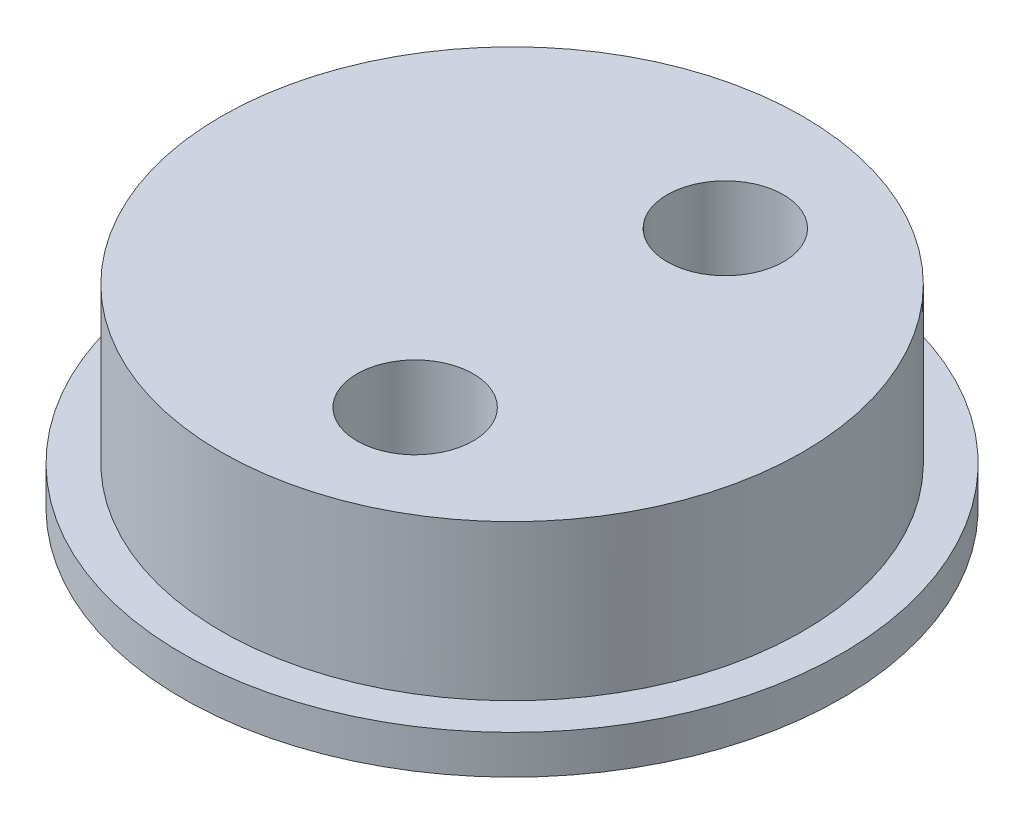
SolidWorks part; units mm, degrees
ref_plane "Front Plane" through (0, 0, 0) normal (0, 0, 1) x (1, 0, 0)
ref_plane "Top Plane" through (0, 0, 0) normal (0, 1, 0) x (1, 0, 0)
ref_plane "Right Plane" through (0, 0, 0) normal (1, 0, 0) x (0, 0, -1)
sketch "Sketch1" plane through (0, 0, 0) normal (0, 1, 0) x (1, 0, 0)
  line L0 (0, 0) -> (-1.5, 0) construction
  circle A1 centre (-1.5, 0) radius 7.5
  point P12 (0, 0)
  dimension "D3" = 15
  dimension "D2" = 1.5
extrude "Boss-Extrude1" add sketch "Sketch1" along normal blind 5
sketch "Sketch2" plane through (0, 0, 0) normal (0, -1, 0) x (1, 0, 0)
  line L0 (-12.8187, 0) -> (7.6603, 0) construction
  circle A0 centre (-1.5, 0) radius 8.5
  dimension "D2" = 17
  dimension "D1" = 1.5
extrude "Boss-Extrude2" add sketch "Sketch2" against normal blind 1
sketch "Sketch4" plane through (0, 5, 0) normal (0, 1, 0) x (1, 0, 0)
  line L0 (0, 8.8969) -> (0, -8.7328) construction
  circle A0 centre (0, 0) radius 4 construction
  circle A1 centre (0, 4) radius 1.5
  circle A2 centre (0, -4) radius 1.5
  dimension "D1" = 8
  dimension "D2" = 3
extrude "Cut-Extrude1" cut sketch "Sketch4" against normal through all
